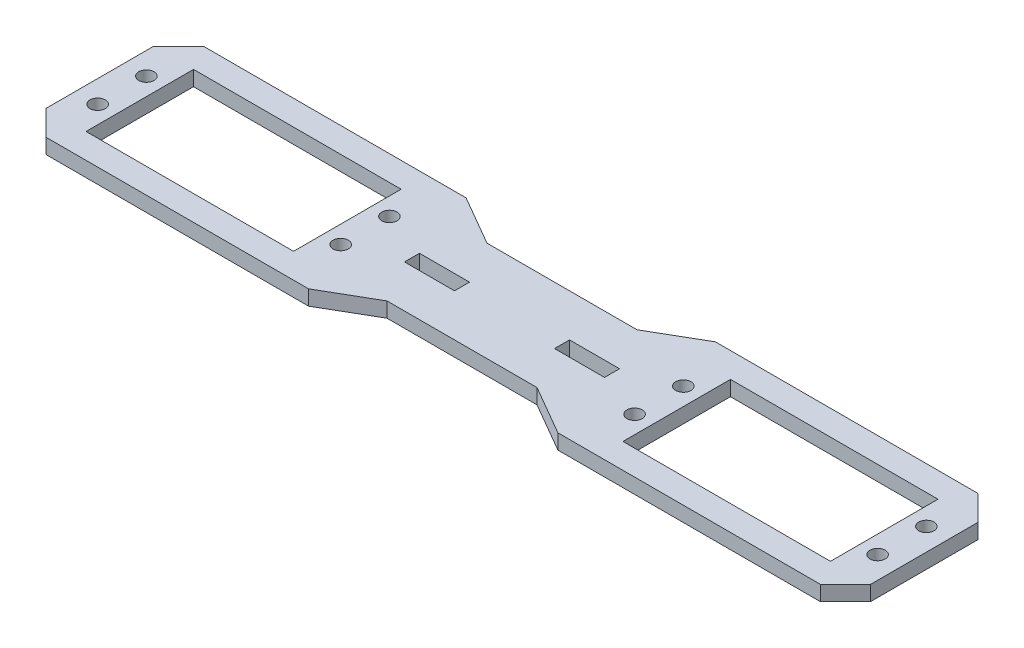
SolidWorks part; units mm, degrees
ref_plane "前视基准面" through (0, 0, 0) normal (0, 0, 1) x (1, 0, 0)
ref_plane "上视基准面" through (0, 0, 0) normal (0, 1, 0) x (1, 0, 0)
ref_plane "右视基准面" through (0, 0, 0) normal (1, 0, 0) x (0, 0, -1)
sketch "草图1" plane through (0, 0, 0) normal (0, 1, 0) x (1, 0, 0)
  line L0 (-92.2198, 0) -> (92.2198, 0) construction
  line L1 (0, 54.1749) -> (0, -54.1749) construction
  line L2 (15, 10) -> (-15, 10)
  line L3 (-15, 10) -> (-24.93, 15.75)
  line L4 (-24.93, 15.75) -> (-77.43, 15.75)
  line L5 (-77.43, 15.75) -> (-82.43, 10.75)
  line L6 (-82.43, 10.75) -> (-82.43, -10.75)
  line L7 (-74.43, -10.75) -> (-74.43, 10.75)
  line L8 (-74.43, 10.75) -> (-32.93, 10.75)
  line L9 (-32.93, 10.75) -> (-32.93, -10.75)
  line L10 (-20, -1.5) -> (-20, 1.5)
  line L11 (-20, 1.5) -> (-10, 1.5)
  line L12 (-10, 1.5) -> (-10, -1.5)
  line L13 (-20, -1.5) -> (-10, -1.5)
  line L14 (-74.43, -10.75) -> (-32.93, -10.75)
  line L15 (-77.43, -15.75) -> (-82.43, -10.75)
  line L16 (-24.93, -15.75) -> (-77.43, -15.75)
  line L17 (-15, -10) -> (-24.93, -15.75)
  line L18 (15, -10) -> (-15, -10)
  line L19 (15, -10) -> (24.93, -15.75)
  line L20 (24.93, -15.75) -> (77.43, -15.75)
  line L21 (77.43, -15.75) -> (82.43, -10.75)
  line L22 (74.43, -10.75) -> (32.93, -10.75)
  line L23 (20, -1.5) -> (10, -1.5)
  line L24 (10, 1.5) -> (10, -1.5)
  line L25 (20, 1.5) -> (10, 1.5)
  line L26 (20, -1.5) -> (20, 1.5)
  line L27 (32.93, 10.75) -> (32.93, -10.75)
  line L28 (74.43, 10.75) -> (32.93, 10.75)
  line L29 (74.43, -10.75) -> (74.43, 10.75)
  line L30 (82.43, 10.75) -> (82.43, -10.75)
  line L31 (77.43, 15.75) -> (82.43, 10.75)
  line L32 (24.93, 15.75) -> (77.43, 15.75)
  line L33 (15, 10) -> (24.93, 15.75)
  circle A0 centre (-77.98, 4.875) radius 1.525
  circle A1 centre (-77.98, -4.875) radius 1.525
  circle A2 centre (77.98, -4.875) radius 1.525
  circle A3 centre (77.98, 4.875) radius 1.525
  circle A4 centre (-29.38, 4.875) radius 1.525
  circle A5 centre (-29.38, -4.875) radius 1.525
  circle A6 centre (29.38, -4.875) radius 1.525
  circle A7 centre (29.38, 4.875) radius 1.525
  point P0 (82.43, 0)
  point P4 (0, 0)
  point P8 (0, 0)
  point P15 (-53.68, 10.75)
  point P27 (-10, 0)
  point P28 (-20, 0)
  point P29 (-32.93, 0)
  point P30 (-74.43, 0)
  point P31 (-82.43, 0)
  point P40 (0, -10)
  point P55 (0, 10)
  point P56 (74.43, 0)
  point P57 (32.93, 0)
  point P58 (20, 0)
  point P59 (10, 0)
  dimension "D16" = 3.05
  dimension "D17" = 3.05
  dimension "D1" = 31.5
  dimension "D2" = 164.86
  dimension "D3" = 15
  dimension "D4" = 57.5
  dimension "D5" = 5.75
  dimension "D6" = 5
  dimension "D7" = 5
  dimension "D8" = 8
  dimension "D9" = 41.5
  dimension "D10" = 4.45
  dimension "D11" = 45
  dimension "D12" = 9.75
  dimension "D13" = 10
  dimension "D14" = 1.5
  dimension "D15" = 10
  dimension "D18" = 48.6
  dimension "D19" = 9.75
extrude "凸台-拉伸1" add sketch "草图1" along normal blind 3
